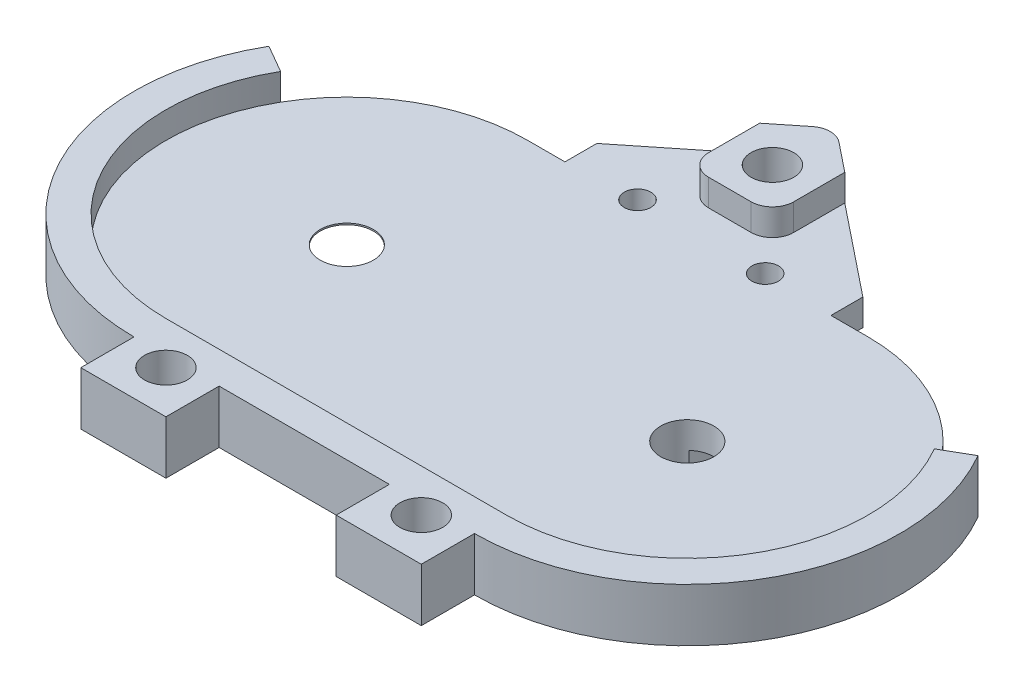
SolidWorks part; units mm, degrees
material "PLA"
ref_plane "Front Plane" through (0, 0, 0) normal (0, 0, 1) x (1, 0, 0)
ref_plane "Top Plane" through (0, 0, 0) normal (0, 1, 0) x (1, 0, 0)
ref_plane "Right Plane" through (0, 0, 0) normal (1, 0, 0) x (0, 0, -1)
sketch "Sketch1" plane through (0, 0, 0) normal (0, 1, 0) x (1, 0, 0)
  line L0 (-40.64, 0) -> (40.64, 0) construction
  line L1 (0, 34.29) -> (0, -31.75) construction
  line L2 (20.32, 0) -> (7.62, 21.997) construction
  line L3 (-20.32, 0) -> (-7.62, 21.997) construction
  line L11 (-20.32, 25.4) -> (-15.875, 25.4)
  line L16 (20.32, 25.4) -> (15.875, 25.4)
  line L17 (-20.32, -25.4) -> (-20.32, -31.75)
  line L18 (-20.32, -31.75) -> (20.32, -31.75)
  line L19 (20.32, -31.75) -> (20.32, -25.4)
  line L22 (-15.875, 25.4) -> (0, 38.1)
  line L23 (0, 38.1) -> (15.875, 25.4)
  circle A3 centre (20.32, 0) radius 3.175
  circle A4 centre (7.62, 21.997) radius 1.5875
  circle A5 centre (-20.32, 0) radius 3.175
  circle A6 centre (-7.62, 21.997) radius 1.5875
  arc A10 (-20.32, 25.4) -> (-20.32, -25.4) centre (-20.32, 0) ccw
  arc A11 (20.32, 25.4) -> (20.32, -25.4) centre (20.32, 0) cw
  dimension "D1" = 25.4
  dimension "D4" = 6.35
  dimension "D5" = 3.175
  dimension "D6" = 25.4
  dimension "D2" = 60
  dimension "D3" = 20.32
  dimension "D7" = 12.7
  dimension "D8" = 31.75
  dimension "D9" = 6.35
extrude "Boss-Extrude1" add sketch "Sketch1" along normal blind 3.175
sketch "Sketch4" [suppressed] plane through (0, 3.175, 0) normal (0, 1, 0) x (1, 0, 0)
  line L1 (-20.32, -25.4) -> (-20.32, -31.75) construction
  line L2 (-20.32, -31.75) -> (20.32, -31.75) construction
  line L3 (20.32, -31.75) -> (20.32, -25.4) construction
  point P0 (-7.62, 21.997)
  point P1 (0, 21.997)
  point P2 (20.32, 0)
  point P4 (7.62, -25.4)
  point P8 (7.62, 21.997)
  point P9 (-20.32, 0)
  point P10 (-7.62, -25.4)
  dimension "D1" = 12.7
  dimension "D2" = 6.35
  dimension "D3" = 12.7
  dimension "D4" = 7.62
hole_wizard "#10 (0.1935) Diameter Hole1" [suppressed] positions "Sketch5" profile "Sketch6" hole size "#10" standard "ANSI Inch"
sketch "Sketch5" [suppressed] plane through (0, 3.175, 0) normal (0, 1, 0) x (1, 0, 0)
  point P6 (0, 21.997)
  point P9 (0, 21.997)
  point P11 (-7.62, -25.4)
  point P14 (7.62, -25.4)
sketch "Sketch6" plane through (0, 3.175, -21.997) normal (1, 0, 0) x (0, 0, 1)
  line L0 (0, 0) -> (0, 3.175)
  line L1 (0, 3.175) -> (2.4574, 3.175)
  line L2 (2.4574, 3.175) -> (2.4574, 0)
  line L5 (2.4574, 0) -> (0, 0)
  line L11 (0, -6.35) -> (0, 107.95) construction
  dimension "Thru Hole Dia." = 4.9149
  dimension "Thru Hole Depth" = 3.175
sketch "Sketch7" plane through (0, 3.175, 0) normal (0, 1, 0) x (1, 0, 0)
  line L0 (0, 0) -> (0, 33.9313) construction
  line L1 (-20.32, 0) -> (-42.317, 12.7)
  line L2 (0, 0) -> (-20.32, 0) construction
  line L3 (-15.875, 25.4) -> (-20.32, 25.4)
  line L4 (-20.32, 21.59) -> (-15.875, 21.59)
  line L5 (-15.875, 21.59) -> (-15.875, 25.4)
  circle A0 centre (-20.32, 0) radius 25.4
  arc A1 (-20.32, 25.4) -> (-20.32, -25.4) centre (-20.32, 0) ccw construction
  circle A2 centre (-20.32, 0) radius 21.59
  line M9 (-15.875, 25.4) -> (-20.32, 25.4)
  arc M10 (-20.32, 25.4) -> (-20.32, -25.4) centre (-20.32, 0) ccw
  dimension "D1" = 43.18
  dimension "D2" = 150
extrude "Cut-Extrude1" cut sketch "Sketch7" against normal up to next contours A2 L4 L5 A0 L1 M10 | A0 L5 M9
sketch "Sketch9" plane through (0, 3.175, 0) normal (0, 1, 0) x (1, 0, 0)
  line L0 (-39.0175, 10.795) -> (-42.317, 12.7)
  line L1 (0, 38.1) -> (-5.08, 34.036)
  line L2 (-20.32, -25.4) -> (-20.32, -31.75)
  line L3 (-20.32, -31.75) -> (-10.16, -31.75)
  line L5 (-20.32, -21.59) -> (0, -21.59)
  line L6 (0, -21.59) -> (0, -25.4)
  line L12 (0, 25.4) -> (-5.08, 25.4)
  line L13 (-5.08, 25.4) -> (-5.08, 34.036)
  line L14 (0, 25.4) -> (0, 38.1)
  line L15 (0, -25.4) -> (-10.16, -25.4)
  line L16 (-10.16, -25.4) -> (-10.16, -31.75)
  line L17 (-15.875, 25.4) -> (0, 38.1) construction
  arc A0 (-42.317, 12.7) -> (-20.32, -25.4) centre (-20.32, 0) ccw
  arc A1 (-39.0175, 10.795) -> (-20.32, -21.59) centre (-20.32, 0) ccw
  arc A2 (-42.317, 12.7) -> (-20.32, -25.4) centre (-20.32, 0) ccw construction
  arc A3 (-20.32, 21.59) -> (-39.0175, 10.795) centre (-20.32, 0) ccw construction
  dimension "D1" = 5.08
  dimension "D2" = 57.15
  dimension "D3" = 10.16
extrude "Boss-Extrude2" add sketch "Sketch9" along normal blind 3.175
mirror "Mirror1" about plane through (0, 0, 0) normal (1, 0, 0) of "Boss-Extrude2", "Cut-Extrude1"
sketch "Sketch13" plane through (0, 6.35, 0) normal (0, 1, 0) x (1, 0, 0)
  line L0 (0, 0) -> (0, -5.6853) construction
  line L2 (5.08, 25.4) -> (-5.08, 25.4) construction
  line L3 (-20.32, -31.75) -> (-10.16, -31.75) construction
  point P0 (0, 30.48)
  point P1 (-15.24, -26.67)
  point P10 (15.24, -26.67)
  dimension "D1" = 15.24
  dimension "D2" = 5.08
  dimension "D3" = 5.08
hole_wizard "Tap Drill for #10 Helicoil2" positions "Sketch14" profile "Sketch15" hole size "#10-32" standard "ANSI Inch" end condition up to next
sketch "Sketch14" plane through (0, 6.35, 0) normal (0, 1, 0) x (1, 0, 0)
  point P0 (-15.24, -26.67)
  point P3 (15.24, -26.67)
  point P6 (0, 30.48)
sketch "Sketch15" plane through (-15.24, 6.35, 26.67) normal (1, 0, 0) x (0, 0, 1)
  line L0 (0, 0) -> (0, 6.35)
  line L1 (0, 6.35) -> (2.5527, 6.35)
  line L2 (2.5527, 6.35) -> (2.5527, 0)
  line L5 (2.5527, 0) -> (0, 0)
  line L11 (0, -6.35) -> (0, 107.95) construction
  dimension "Thru Hole Dia." = 5.1054
  dimension "Thru Hole Depth" = 6.35
fillet "Fillet1" radius 2.54 3 edges at (0, 3.175, -38.1) (5.08, 4.7625, -25.4) (-5.08, 4.7625, -25.4)
sketch "Sketch16" plane through (0, 3.175, 0) normal (0, 1, 0) x (1, 0, 0)
  line L0 (-39.0175, 10.795) -> (-50.016, 17.145)
  line L1 (-50.016, 17.145) -> (-55.096, 8.3462)
  line L2 (-55.096, 8.3462) -> (-44.0975, 1.9962)
  line L3 (-44.0975, 1.9962) -> (-39.0175, 10.795)
  line L4 (-39.0175, 10.795) -> (-42.317, 12.7) construction
  line L5 (0, 0) -> (0, -14.9889) construction
  line L6 (10.16, -25.4) -> (-10.16, -25.4) construction
  line L7 (5.08, -35.56) -> (-5.08, -35.56)
  line L9 (5.08, -25.4) -> (-5.08, -25.4)
  line L11 (5.08, -35.56) -> (-5.08, -25.4) construction
  line L12 (5.08, -25.4) -> (-5.08, -35.56) construction
  line L13 (-5.08, -35.56) -> (-10.16, -31.75)
  line L14 (-10.16, -31.75) -> (-5.08, -25.4)
  line L15 (5.08, -35.56) -> (10.16, -31.75)
  line L16 (10.16, -31.75) -> (5.08, -25.4)
  line L17 (44.0975, 1.9962) -> (39.0175, 10.795)
  line L18 (55.096, 8.3462) -> (44.0975, 1.9962)
  line L19 (50.016, 17.145) -> (55.096, 8.3462)
  line L20 (39.0175, 10.795) -> (50.016, 17.145)
  point P9 (0, -30.48)
  point P18 (0, -25.4)
  dimension "D1" = 10.16
  dimension "D2" = 12.7
  dimension "D3" = 10.16
  dimension "D4" = 10.16
extrude "Boss-Extrude3" [suppressed] add sketch "Sketch16" against normal up to surface (3.175 mm away)
fillet "Fillet2" [suppressed] radius 6.35
sketch "Sketch17" [suppressed] plane through (0, 3.175, 0) normal (0, 1, 0) x (1, 0, 0)
  line L0 (-50.016, 17.145) -> (-55.096, 8.3462) construction
  line L1 (-42.317, 12.7) -> (-50.016, 17.145) construction
  line L2 (-2.9633, -35.56) -> (2.9633, -35.56) construction
  line L3 (0, 0) -> (0, -30.48) construction
  point P0 (-48.1566, 10.2056)
  point P1 (0, -30.48)
  point P11 (48.1566, 10.2056)
  dimension "D1" = 5.08
  dimension "D2" = 5.08
  dimension "D3" = 5.08
hole_wizard "Tap Drill for #10 Helicoil3" [suppressed] positions "Sketch18" profile "Sketch19" hole size "#10-32" standard "ANSI Inch"
sketch "Sketch18" [suppressed] plane through (0, 3.175, 0) normal (0, 1, 0) x (1, 0, 0)
  point P0 (-48.1566, 10.2056)
  point P3 (0, -30.48)
  point P6 (48.1566, 10.2056)
sketch "Sketch19" plane through (-48.1566, 3.175, -10.2056) normal (1, 0, 0) x (0, 0, 1)
  line L0 (0, 0) -> (0, 3.175)
  line L1 (0, 3.175) -> (2.5527, 3.175)
  line L2 (2.5527, 3.175) -> (2.5527, 0)
  line L5 (2.5527, 0) -> (0, 0)
  line L11 (0, -6.35) -> (0, 107.95) construction
  dimension "Thru Hole Dia." = 5.1054
  dimension "Thru Hole Depth" = 3.175
sketch "Sketch20" plane through (0, 3.175, 0) normal (0, 1, 0) x (1, 0, 0)
  line L1 (-10.16, -31.75) -> (10.16, -31.75)
  line L2 (-10.16, -31.75) -> (-10.16, -25.4)
  line L3 (-10.16, -25.4) -> (10.16, -25.4)
  line L4 (10.16, -31.75) -> (10.16, -25.4)
extrude "Cut-Extrude2" cut sketch "Sketch20" against normal up to next
sketch "Sketch22" plane through (0, 0, 0) normal (0, -1, 0) x (1, 0, 0)
  circle A0 centre (-20.32, 0) radius 11.5
  dimension "D1" = 23
extrude "Cut-Extrude3" cut sketch "Sketch22" against normal blind 3
sketch "Sketch23" plane through (0, 0, 0) normal (0, -1, 0) x (1, 0, 0)
  line L0 (-32.32, 0) -> (12.68, 0) construction
  line L5 (-29.32, 12.25) -> (9.68, 12.25)
  line L26 (-32.32, 9.25) -> (-32.32, -9.25)
  line L27 (-29.32, -12.25) -> (9.68, -12.25)
  line L28 (12.68, 9.25) -> (12.68, -9.25)
  line L29 (18.18, -2.3454) -> (18.18, -12.75)
  line L30 (-29.32, 17.75) -> (13.18, 17.75)
  line L31 (-34.32, 12.75) -> (-34.32, -12.75)
  line L32 (-29.32, -17.75) -> (13.18, -17.75)
  line L33 (18.18, 12.75) -> (18.18, 2.3454)
  arc A4 (13.18, -17.75) -> (18.18, -12.75) centre (13.18, -12.75) ccw
  arc A5 (13.18, 17.75) -> (18.18, 12.75) centre (13.18, 12.75) cw
  circle A6 centre (-20.32, 0) radius 3.175 construction
  arc A7 (-29.32, 17.75) -> (-34.32, 12.75) centre (-29.32, 12.75) ccw
  arc A8 (-34.32, -12.75) -> (-29.32, -17.75) centre (-29.32, -12.75) ccw
  arc A9 (9.68, -12.25) -> (12.68, -9.25) centre (9.68, -9.25) ccw
  arc A10 (9.68, 12.25) -> (12.68, 9.25) centre (9.68, 9.25) cw
  arc A11 (-29.32, 12.25) -> (-32.32, 9.25) centre (-29.32, 9.25) ccw
  arc A12 (-32.32, -9.25) -> (-29.32, -12.25) centre (-29.32, -9.25) ccw
  arc A13 (18.18, 2.3454) -> (18.18, -2.3454) centre (20.32, 0) ccw
  point P24 (12.68, 12.25)
  point P27 (-32.32, 12.25)
  point P30 (-32.32, -12.25)
  dimension "D6" = 5.5
  dimension "D3" = 12
  dimension "D8" = 5
  dimension "D9" = 3
  dimension "D1" = 24.5
  dimension "D2" = 45
  dimension "D4" = 2
  dimension "D5" = 5.5
  dimension "D7" = 5.5
extrude "Boss-Extrude4" add sketch "Sketch23" along normal blind 2.75
